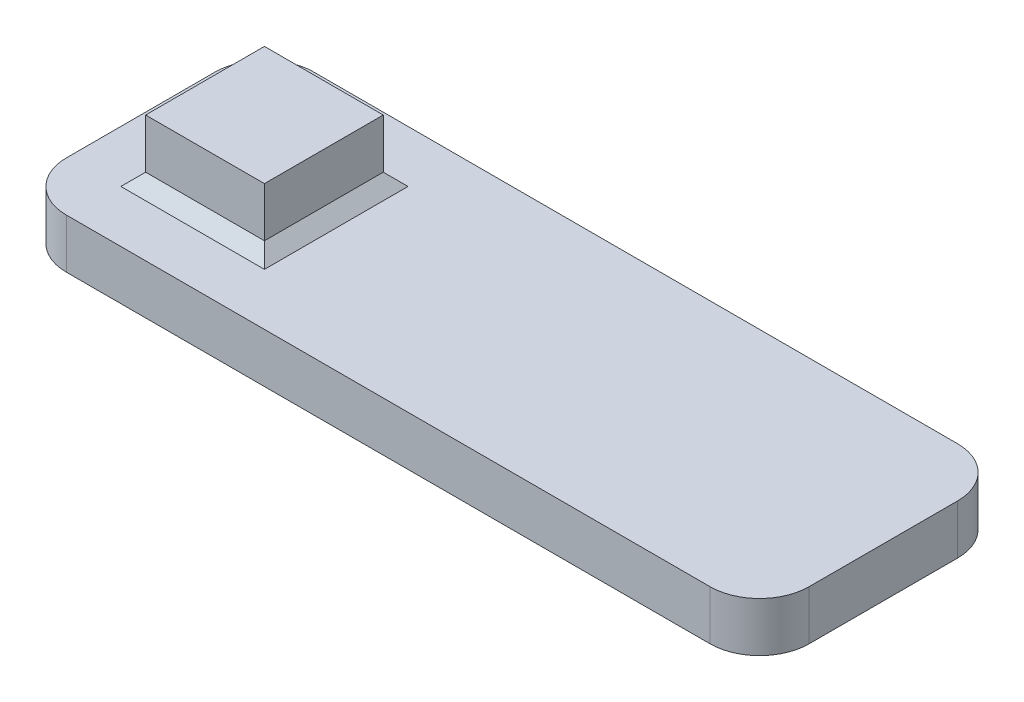
SolidWorks part; units mm, degrees
ref_plane "Plano frontal" through (0, 0, 0) normal (0, 0, 1) x (1, 0, 0)
ref_plane "Plano superior" through (0, 0, 0) normal (0, 1, 0) x (1, 0, 0)
ref_plane "Plano direito" through (0, 0, 0) normal (1, 0, 0) x (0, 0, -1)
sketch "Esboço3" plane through (0, 0, 0) normal (0, 1, 0) x (1, 0, 0)
  line L1 (0, 0) -> (30, 0)
  line L2 (0, 0) -> (0, 10)
  line L3 (0, 10) -> (30, 10)
  line L4 (30, 0) -> (30, 10)
  dimension "D1" = 10
  dimension "D2" = 30
extrude "Ressalto-extrusão3" add sketch "Esboço3" along normal blind 2
sketch "Esboço4" plane through (0, 2, 0) normal (0, 1, 0) x (1, 0, 0)
  line L0 (-2.1038, 5) -> (32.2007, 5) construction
  line L2 (2.6, 7.4) -> (7.4, 7.4)
  line L3 (2.6, 7.4) -> (2.6, 2.6)
  line L4 (2.6, 2.6) -> (7.4, 2.6)
  line L5 (7.4, 7.4) -> (7.4, 2.6)
  line L6 (2.6, 7.4) -> (7.4, 2.6) construction
  line L7 (2.6, 2.6) -> (7.4, 7.4) construction
  point P2 (5, 5)
  dimension "D1" = 5
  dimension "D2" = 5
  dimension "D3" = 4.8
  dimension "D4" = 4.8
extrude "Ressalto-extrusão4" add sketch "Esboço4" along normal blind 2.5
chamfer "Chanfro2" distance 0.5 angle 45 4 edges at (7.4, 2, -5) (5, 2, -7.4) (2.6, 2, -5) (5, 2, -2.6)
fillet "Filete5" radius 2 1 edges at (0, 1, 0)
fillet "Filete6" radius 2 1 edges at (0, 1, -10)
fillet "Filete7" radius 2 1 edges at (30, 1, -10)
fillet "Filete8" radius 2 1 edges at (30, 1, 0)
